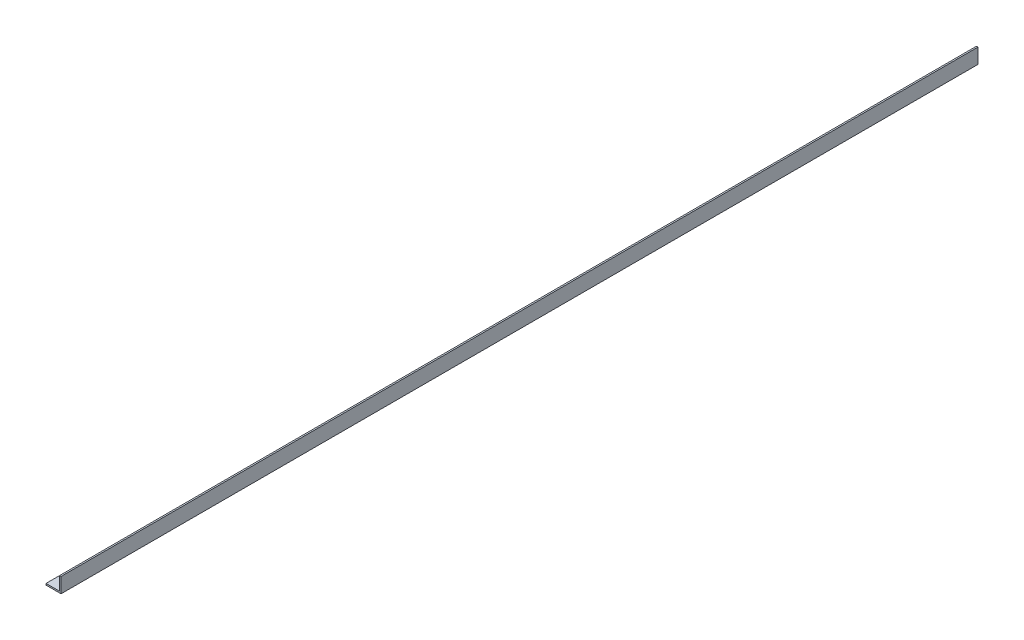
SolidWorks part; units mm, degrees
ref_plane "Front Plane" through (0, 0, 0) normal (0, 0, 1) x (1, 0, 0)
ref_plane "Top Plane" through (0, 0, 0) normal (0, 1, 0) x (1, 0, 0)
ref_plane "Right Plane" through (0, 0, 0) normal (1, 0, 0) x (0, 0, -1)
sketch "Sketch1" plane through (0, 0, 0) normal (0, 0, 1) x (1, 0, 0)
  line L0 (-10, 0) -> (0, 0)
  line L1 (0, 0) -> (0, 10)
  line L2 (0, 10) -> (-1, 10)
  line L3 (-1, 10) -> (-1, 1)
  line L4 (-1, 1) -> (-10, 1)
  line L5 (-10, 0) -> (-10, 1)
  line L6 (-0.5, 10) -> (0, 10) construction
  line L7 (-10, 0.5) -> (-10, 0) construction
  dimension "Vert" = 10
  dimension "Horz" = 10
  dimension "Thickness" = 1
sketch "Sketch2" plane through (0, 0, 0) normal (1, 0, 0) x (0, 0, -1)
  line L0 (-304.8, 0) -> (304.8, 0) construction
  point P0 (-292.608, 0)
  point P4 (0, 0)
  point P5 (292.608, 0)
  dimension "Length" = 609.6
  dimension "D1" = 12.192
  dimension "D2" = 12.192
sketch "Sketch3" plane through (0, 0, 0) normal (0, 0, 1) x (1, 0, 0)
  line L0 (-10, 0) -> (0, 0) construction
  line L1 (0, 0) -> (0, 10) construction
  line L2 (0, 10) -> (-1, 10) construction
  line L3 (-1, 10) -> (-1, 1) construction
  line L4 (-1, 1) -> (-10, 1) construction
  line L5 (-10, 0) -> (-10, 1) construction
  line L6 (-10, 0) -> (0, 0)
  line L7 (0, 0) -> (0, 10)
  line L8 (0, 10) -> (-1, 10)
  line L9 (-1, 10) -> (-1, 1)
  line L10 (-1, 1) -> (-10, 1)
  line L11 (-10, 0) -> (-10, 1)
extrude "Boss-Extrude1" add sketch "Sketch3" along normal up to vertex (304.8 mm away) and the other way up to vertex (304.8 mm away) up to point (0, 0, 304.8) other way up to point (0, 0, -304.8)
equation "\"D1@Sketch2\"=\"Length@Sketch2\"*.02"
equation "\"D2@Sketch2\"=\"D1@Sketch2\""
